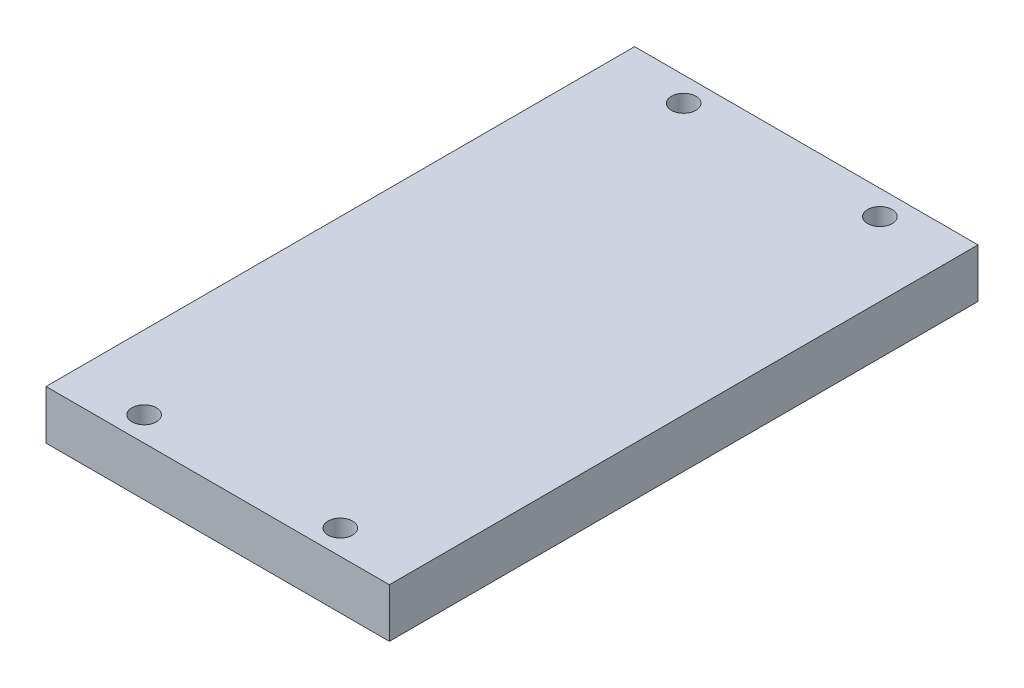
SolidWorks part; units mm, degrees
ref_plane "Front Plane" through (0, 0, 0) normal (0, 0, 1) x (1, 0, 0)
ref_plane "Top Plane" through (0, 0, 0) normal (0, 1, 0) x (1, 0, 0)
ref_plane "Right Plane" through (0, 0, 0) normal (1, 0, 0) x (0, 0, -1)
sketch "Sketch1" plane through (0, 0, 0) normal (0, 1, 0) x (1, 0, 0)
  line L1 (-21, 36) -> (21, 36)
  line L2 (-21, 36) -> (-21, -36)
  line L3 (-21, -36) -> (21, -36)
  line L4 (21, 36) -> (21, -36)
  line L5 (-21, 36) -> (21, -36) construction
  line L6 (-21, -36) -> (21, 36) construction
  point P0 (0, 0)
  dimension "D1" = 42
  dimension "D2" = 72
extrude "Boss-Extrude1" add sketch "Sketch1" along normal blind 6
sketch "Sketch2" plane through (0, 6, 0) normal (0, 1, 0) x (1, 0, 0)
  line L0 (0, 0) -> (0, -42.4327) construction
  line L1 (0, 0) -> (-28.4874, 0) construction
  line L3 (-21, -36) -> (21, -36) construction
  circle A0 centre (-12, -33) radius 1.5
  circle A3 centre (12, -33) radius 1.5
  circle A4 centre (12, 33) radius 1.5
  circle A7 centre (-12, 33) radius 1.5
  dimension "D4" = 3
  dimension "D6" = 3
  dimension "D5" = 12
extrude "Cut-Extrude1" cut sketch "Sketch2" against normal blind 10
